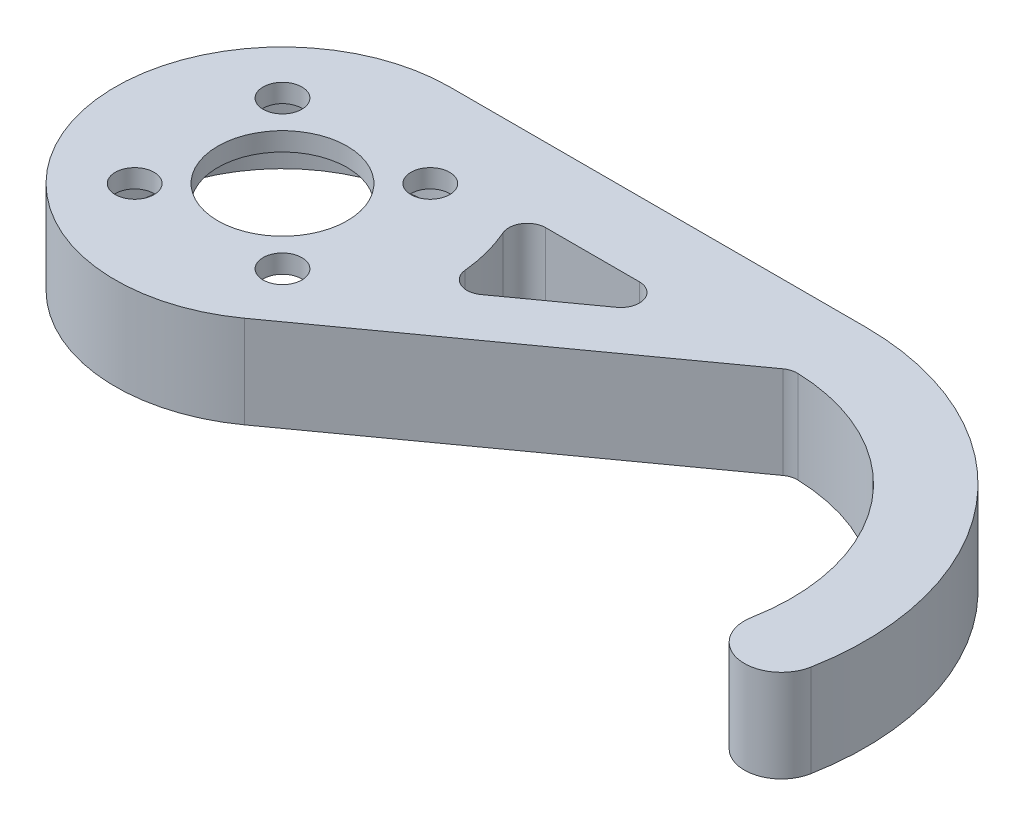
SolidWorks part; units mm, degrees
ref_plane "Front Plane" through (0, 0, 0) normal (0, 0, 1) x (1, 0, 0)
ref_plane "Top Plane" through (0, 0, 0) normal (0, 1, 0) x (1, 0, 0)
ref_plane "Right Plane" through (0, 0, 0) normal (1, 0, 0) x (0, 0, -1)
sketch "Sketch1" plane through (0, 0, 0) normal (0, 1, 0) x (1, 0, 0)
  line L0 (0, 18.1) -> (45, 18.1)
  line L1 (15.02, 10.1) -> (34.7323, 10.1)
  line L2 (0, -20) -> (80.4705, -20) construction
  line L3 (0, -18.1) -> (70, -16) construction
  line L4 (45, 10.1) -> (10.5769, -14.6881)
  line L5 (-8, -8) -> (8, -8) construction
  line L6 (-8, -8) -> (-8, 8) construction
  line L7 (-8, 8) -> (8, 8) construction
  line L8 (8, -8) -> (8, 8) construction
  line L9 (0, 8) -> (0, -8) construction
  line L10 (-8, 0) -> (8, 0) construction
  line L11 (34.7323, 10.1) -> (17.9943, -1.953)
  circle A0 centre (0, 0) radius 16 construction
  arc A1 (0, 18.1) -> (10.5769, -14.6881) centre (0, 0) ccw
  arc A2 (45, 18.1) -> (73.932, -16.7342) centre (45, -11.3321) cw
  arc A3 (45, 10.1) -> (66.068, -15.2658) centre (45, -11.3321) cw
  arc A4 (45, 10.1) -> (66.068, -15.2658) centre (45, -11.3321) cw construction
  arc A5 (66.068, -15.2658) -> (73.932, -16.7342) centre (70, -16) ccw
  circle A6 centre (-8, 8) radius 2 construction
  circle A7 centre (8, 8) radius 2 construction
  circle A8 centre (8, -8) radius 2 construction
  circle A9 centre (-8, -8) radius 2 construction
  circle A10 centre (-8, 8) radius 2.1
  circle A11 centre (8, 8) radius 2.1
  circle A12 centre (8, -8) radius 2.1
  circle A13 centre (-8, -8) radius 2.1
  circle A14 centre (0, 0) radius 7
  arc A15 (17.9943, -1.953) -> (15.02, 10.1) centre (0, 0) ccw
  point P32 (10.7906, -14.5318)
  point P33 (34.2003, 10.1)
  point P34 (28.6224, 10.1)
  point P35 (0, 0)
  dimension "D1" = 32
  dimension "D2" = 36.2
  dimension "D9" = 4
  dimension "D10" = 4.2
  dimension "D11" = 14
  dimension "D3" = 8
  dimension "D5" = 20
  dimension "D6" = 45
  dimension "D7" = 70
  dimension "D8" = 16
  dimension "D12" = 6
  dimension "D4" = 8
extrude "Boss-Extrude1" add sketch "Sketch1" along normal blind 10
fillet "Fillet1" radius 2 4 edges at (17.9943, 5, 1.953) (34.7323, 5, -10.1) (15.02, 5, -10.1) (45, 5, -10.1)
sketch "Sketch2" plane through (0, 0, 0) normal (0, -1, 0) x (1, 0, 0)
  circle A0 centre (0, 0) radius 16.1
  dimension "D1" = 32.2
extrude "Cut-Extrude1" cut sketch "Sketch2" against normal blind 8
equation "\"shrinkage\"= .2"
equation "\"D2@Sketch1\"=\"shrinkage\"+32+4"
equation "\"D10@Sketch1\"=\"shrinkage\"+4"
equation "\"D1@Sketch2\"=\"shrinkage\"+32"
equation "\"length\"=45"
equation "\"D6@Sketch1\"=\"length\""
equation "\"D7@Sketch1\"=\"length\"+25"
